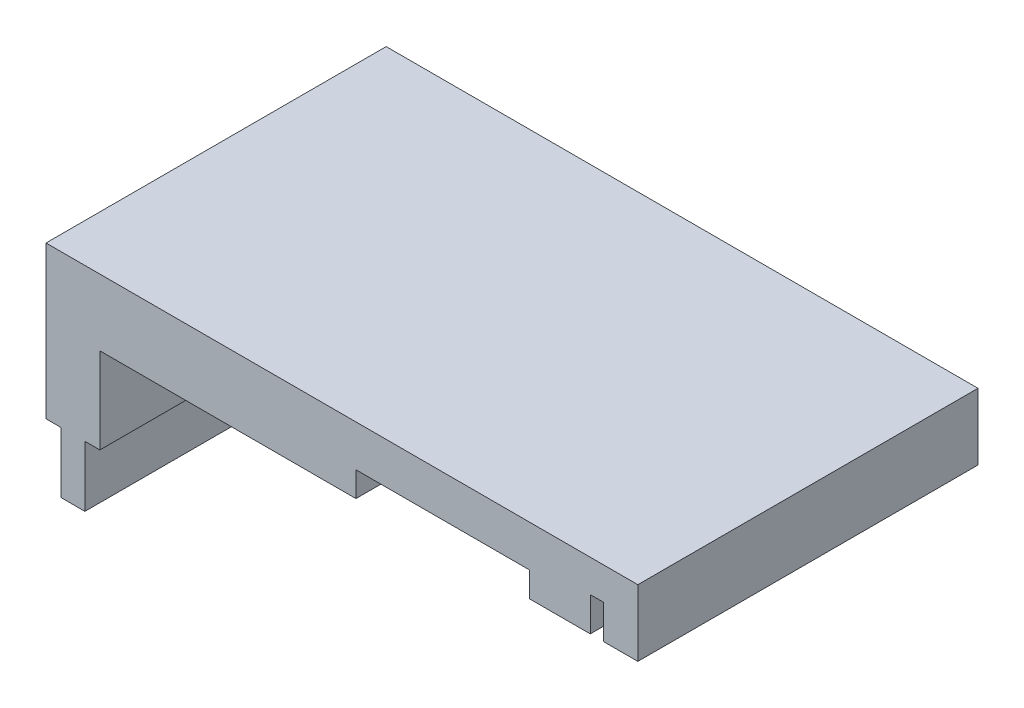
SolidWorks part; units mm, degrees
ref_plane "Front Plane" through (0, 0, 0) normal (0, 0, 1) x (1, 0, 0)
ref_plane "Top Plane" through (0, 0, 0) normal (0, 1, 0) x (1, 0, 0)
ref_plane "Right Plane" through (0, 0, 0) normal (1, 0, 0) x (0, 0, -1)
sketch "Sketch1" plane through (0, 0, 0) normal (0, 0, 1) x (1, 0, 0)
  line L0 (0, 0) -> (0, 18.61)
  line L1 (0, 18.61) -> (-165.72, 18.61)
  line L2 (-165.72, 18.61) -> (-165.72, -24.03)
  line L3 (-165.72, -24.03) -> (-161.52, -24.03)
  line L4 (-161.52, -24.03) -> (-161.52, -41.03)
  line L5 (-161.52, -41.03) -> (-154.83, -41.03)
  line L6 (-154.83, -41.03) -> (-154.83, -24.03)
  line L7 (-154.83, -24.03) -> (-150.63, -24.03)
  line L8 (-150.63, -24.03) -> (-150.63, 0.01)
  line L9 (-150.63, 0.01) -> (-78.94, 0.01)
  line L10 (-78.94, 0.01) -> (-78.94, 7.01)
  line L11 (-78.94, 7.01) -> (-30.27, 7.01)
  line L12 (-30.27, 7.01) -> (-30.27, 0.01)
  line L13 (-30.27, 0.01) -> (-13.32, 0.01)
  line L14 (-13.32, 0.01) -> (-13.32, 9.54)
  line L15 (-13.32, 9.54) -> (-9.63, 9.54)
  line L16 (-9.63, 9.54) -> (-9.63, 0)
  line L17 (-9.63, 0) -> (0, 0)
  dimension "D1" = 6.69
  dimension "D2" = 18.61
  dimension "D3" = 17
  dimension "D4" = 42.64
  dimension "D5" = 24.04
  dimension "D6" = 165.72
  dimension "D7" = 48.67
  dimension "D8" = 7
  dimension "D9" = 16.95
  dimension "D10" = 9.53
  dimension "D11" = 3.69
  dimension "D12" = 4.2
  dimension "D13" = 71.69
extrude "Boss-Extrude1" add sketch "Sketch1" along normal blind 95.25
ref_plane "Plane1" through (-165.72, 18.61, 0) normal (0, 0, -1) x (-1, 0, 0)
sketch "Sketch3" plane through (-150.63, 0, 0) normal (1, 0, 0) x (0, 0, -1)
  line L0 (-95.25, -41.03) -> (0, -41.03) construction
  line L1 (0, 0) -> (-9, 0)
  line L2 (0, 0) -> (0, -41.03)
  line L3 (0, -41.03) -> (-9, -41.03)
  line L4 (-9, 0) -> (-9, -41.03)
  dimension "D1" = 9
extrude "Cut-Extrude1" cut sketch "Sketch3" against normal through all
sketch "Sketch4" plane through (0, 7.01, 0) normal (0, -1, 0) x (1, 0, 0)
  line L0 (-78.94, 95.25) -> (-30.27, 95.25) construction
  line L1 (-30.27, 95.25) -> (-30.27, 0) construction
  circle A0 centre (-69.08, 42.44) radius 1.03
  circle A1 centre (-49.58, 60.2) radius 1.03
  dimension "D1" = 2.06
  dimension "D3" = 19.31
  dimension "D4" = 19.5
  dimension "D5" = 17.76
  dimension "D2" = 35.05
extrude "Cut-Extrude2" cut sketch "Sketch4" against normal blind 3
